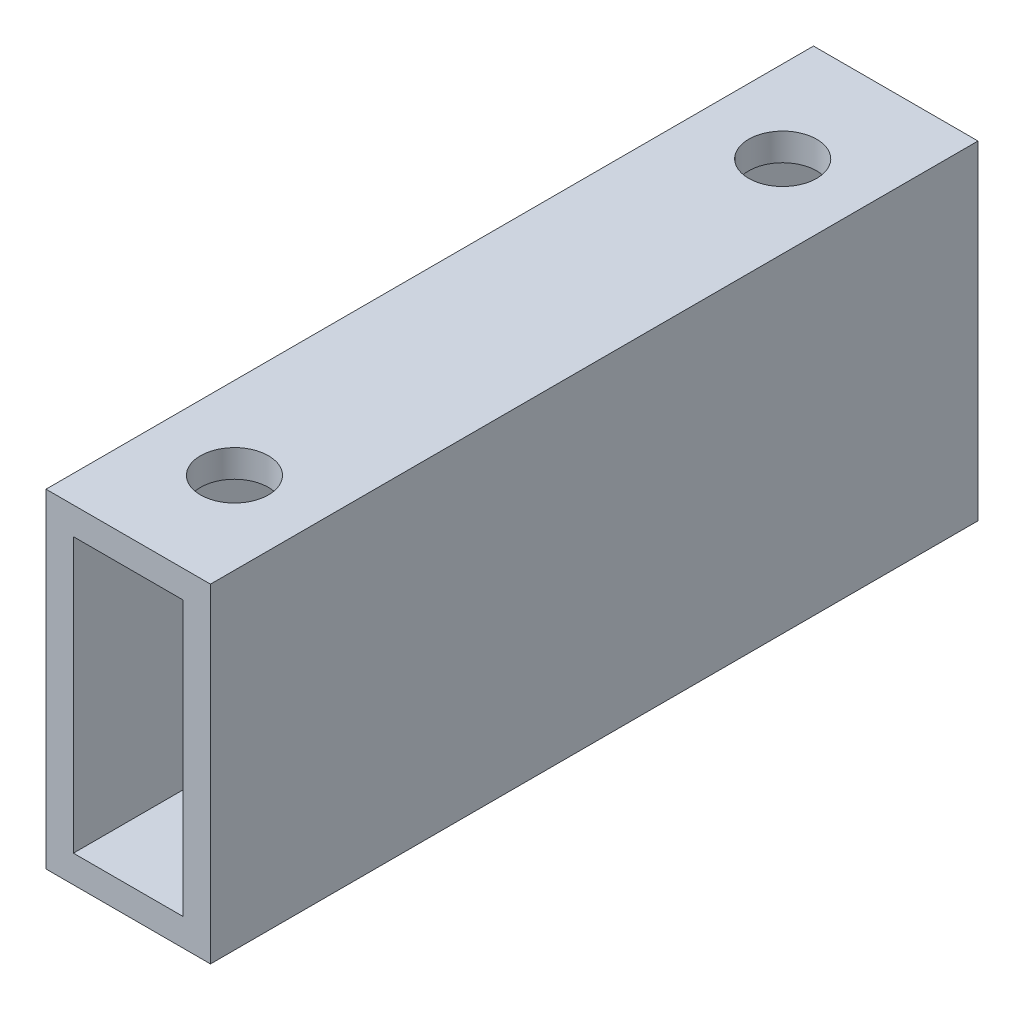
SolidWorks part; units mm, degrees
ref_plane "Front Plane" through (0, 0, 0) normal (0, 0, 1) x (1, 0, 0)
ref_plane "Top Plane" through (0, 0, 0) normal (0, 1, 0) x (1, 0, 0)
ref_plane "Right Plane" through (0, 0, 0) normal (1, 0, 0) x (0, 0, -1)
sketch "Sketch1" plane through (0, 0, 0) normal (0, 0, 1) x (1, 0, 0)
  line L0 (6.35, -15.875) -> (6.35, 15.875)
  line L1 (-9.525, -19.05) -> (9.525, -19.05)
  line L2 (-9.525, -19.05) -> (-9.525, 19.05)
  line L3 (-9.525, 19.05) -> (9.525, 19.05)
  line L4 (9.525, -19.05) -> (9.525, 19.05)
  line L5 (-9.525, -19.05) -> (9.525, 19.05) construction
  line L6 (-9.525, 19.05) -> (9.525, -19.05) construction
  line L7 (-6.35, 15.875) -> (6.35, 15.875)
  line L8 (-6.35, -15.875) -> (-6.35, 15.875)
  line L9 (-6.35, -15.875) -> (6.35, -15.875)
  point P0 (0, 0)
  dimension "D1" = 38.1
  dimension "D2" = 19.05
  dimension "D3" = 3.175
extrude "Boss-Extrude1" add sketch "Sketch1" along normal blind 88.9
sketch "Sketch2" plane through (0, 19.05, 0) normal (0, 1, 0) x (1, 0, 0)
  line L0 (0, -88.9) -> (0, -79.375) construction
  line L1 (9.525, -88.9) -> (-9.525, -88.9) construction
  line L2 (0, -76.5969) -> (0, -13.0969) construction
  circle A0 centre (0, -76.5969) radius 2.7781
  circle A1 centre (0, -13.0969) radius 2.7781
  dimension "D2" = 63.5
  dimension "D3" = 5.5562
  dimension "D1" = 9.525
extrude "Cut-Extrude1" cut sketch "Sketch2" against normal through all
sketch "Sketch3" plane through (0, 19.05, 0) normal (0, 1, 0) x (1, 0, 0)
  circle A0 centre (0, -76.5969) radius 3.937
  circle A1 centre (0, -13.0969) radius 3.937
  dimension "D1" = 7.874
extrude "Cut-Extrude2" cut sketch "Sketch3" against normal up to next
